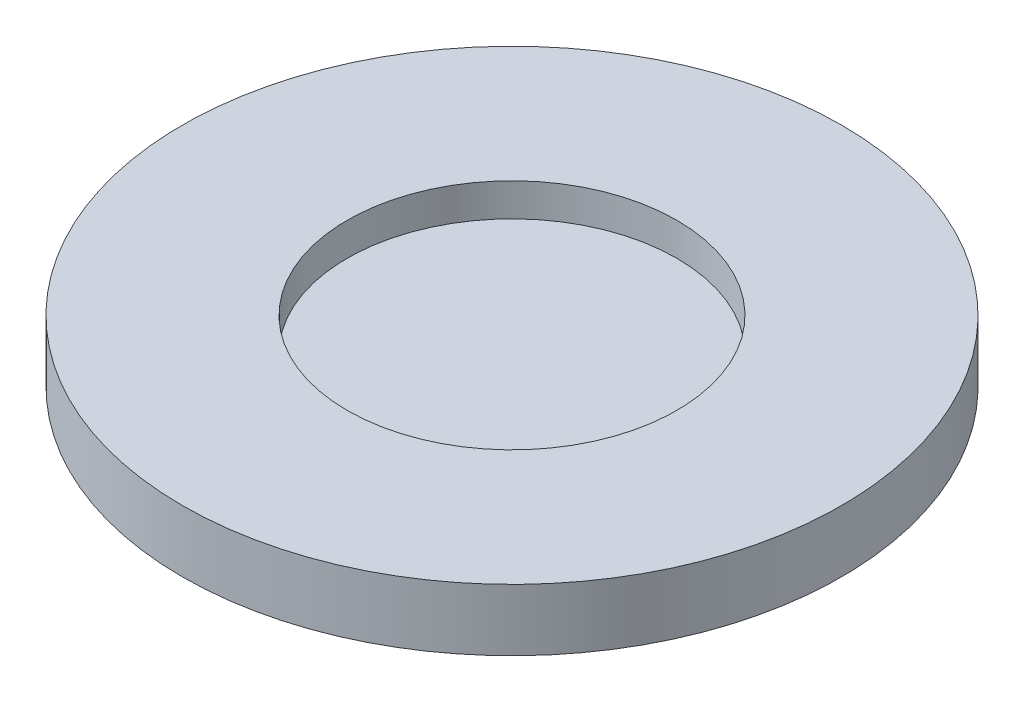
SolidWorks part; units mm, degrees
material "ABS PC"
ref_plane "Front Plane" through (0, 0, 0) normal (0, 0, 1) x (1, 0, 0)
ref_plane "Top Plane" through (0, 0, 0) normal (0, 1, 0) x (1, 0, 0)
ref_plane "Right Plane" through (0, 0, 0) normal (1, 0, 0) x (0, 0, -1)
sketch "Sketch1" plane through (0, 0, 0) normal (0, 1, 0) x (1, 0, 0)
  circle A0 centre (0, 0) radius 25.4
  dimension "D1" = 50.8
extrude "Boss-Extrude1" add sketch "Sketch1" along normal blind 4.7625
sketch "Sketch2" plane through (0, 4.7625, 0) normal (0, 1, 0) x (1, 0, 0)
  circle A0 centre (0, 0) radius 12.7
  dimension "D1" = 25.4
extrude "Cut-Extrude1" cut sketch "Sketch2" against normal blind 2.54
